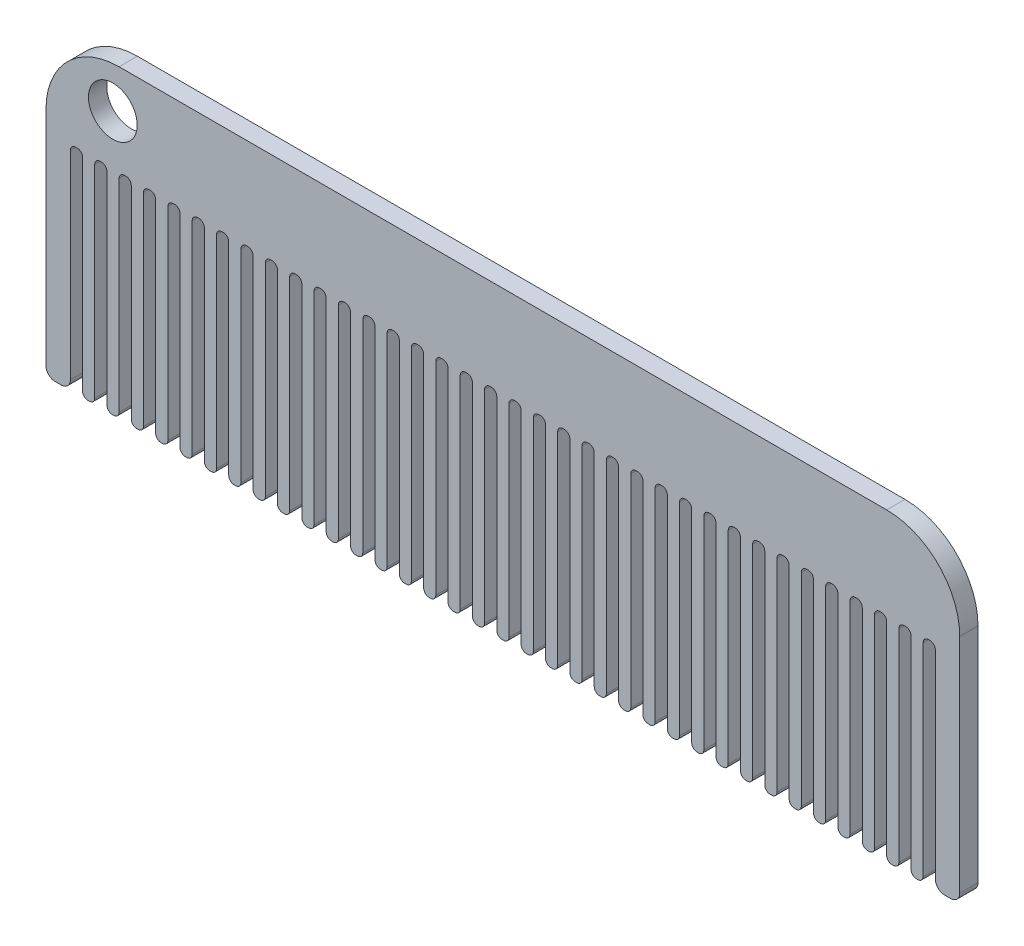
SolidWorks part; units mm, degrees
ref_plane "Plan de face" through (0, 0, 0) normal (0, 0, 1) x (1, 0, 0)
ref_plane "Plan de dessus" through (0, 0, 0) normal (0, 1, 0) x (1, 0, 0)
ref_plane "Plan de droite" through (0, 0, 0) normal (1, 0, 0) x (0, 0, -1)
sketch "Esquisse1" plane through (0, 0, 0) normal (0, 0, 1) x (1, 0, 0)
  line L1 (0, 1.5) -> (0, 38)
  line L2 (12, 50) -> (138, 50)
  line L3 (150, 38) -> (150, 1.5)
  line L4 (1.5, 0) -> (2.5, 0)
  line L5 (4, 1.5) -> (4, 34.12)
  line L6 (4.88, 35) -> (5.12, 35)
  line L7 (6, 34.12) -> (6, 0.88)
  line L8 (6.88, 0) -> (7.12, 0)
  line L9 (8, 0.88) -> (8, 34.12)
  line L10 (8.88, 35) -> (9.12, 35)
  line L11 (10, 34.12) -> (10, 0.88)
  line L12 (10.88, 0) -> (11.12, 0)
  line L13 (12, 0.88) -> (12, 34.12)
  line L14 (12.88, 35) -> (13.12, 35)
  line L15 (14, 34.12) -> (14, 0.88)
  line L16 (14.88, 0) -> (15.12, 0)
  line L17 (16, 0.88) -> (16, 34.12)
  line L18 (16.88, 35) -> (17.12, 35)
  line L19 (18, 34.12) -> (18, 0.88)
  line L20 (18.88, 0) -> (19.12, 0)
  line L21 (20, 0.88) -> (20, 34.12)
  line L22 (20.88, 35) -> (21.12, 35)
  line L23 (22, 34.12) -> (22, 0.88)
  line L24 (22.88, 0) -> (23.12, 0)
  line L25 (24, 0.88) -> (24, 34.12)
  line L26 (24.88, 35) -> (25.12, 35)
  line L27 (26, 34.12) -> (26, 0.88)
  line L28 (26.88, 0) -> (27.12, 0)
  line L29 (28, 0.88) -> (28, 34.12)
  line L30 (28.88, 35) -> (29.12, 35)
  line L31 (30, 34.12) -> (30, 0.88)
  line L32 (30.88, 0) -> (31.12, 0)
  line L33 (32, 0.88) -> (32, 34.12)
  line L34 (32.88, 35) -> (33.12, 35)
  line L35 (34, 34.12) -> (34, 0.88)
  line L36 (34.88, 0) -> (35.12, 0)
  line L37 (36, 0.88) -> (36, 34.12)
  line L38 (36.88, 35) -> (37.12, 35)
  line L39 (38, 34.12) -> (38, 0.88)
  line L40 (38.88, 0) -> (39.12, 0)
  line L41 (40, 0.88) -> (40, 34.12)
  line L42 (40.88, 35) -> (41.12, 35)
  line L43 (42, 34.12) -> (42, 0.88)
  line L44 (42.88, 0) -> (43.12, 0)
  line L45 (44, 0.88) -> (44, 34.12)
  line L46 (44.88, 35) -> (45.12, 35)
  line L47 (46, 34.12) -> (46, 0.88)
  line L48 (46.88, 0) -> (47.12, 0)
  line L49 (48, 0.88) -> (48, 34.12)
  line L50 (48.88, 35) -> (49.12, 35)
  line L51 (50, 34.12) -> (50, 0.88)
  line L52 (50.88, 0) -> (51.12, 0)
  line L53 (52, 0.88) -> (52, 34.12)
  line L54 (52.88, 35) -> (53.12, 35)
  line L55 (54, 34.12) -> (54, 0.88)
  line L56 (54.88, 0) -> (55.12, 0)
  line L57 (56, 0.88) -> (56, 34.12)
  line L58 (56.88, 35) -> (57.12, 35)
  line L59 (58, 34.12) -> (58, 0.88)
  line L60 (58.88, 0) -> (59.12, 0)
  line L61 (60, 0.88) -> (60, 34.12)
  line L62 (60.88, 35) -> (61.12, 35)
  line L63 (62, 34.12) -> (62, 0.88)
  line L64 (62.88, 0) -> (63.12, 0)
  line L65 (64, 0.88) -> (64, 34.12)
  line L66 (64.88, 35) -> (65.12, 35)
  line L67 (66, 34.12) -> (66, 0.88)
  line L68 (66.88, 0) -> (67.12, 0)
  line L69 (68, 0.88) -> (68, 34.12)
  line L70 (68.88, 35) -> (69.12, 35)
  line L71 (70, 34.12) -> (70, 0.88)
  line L72 (70.88, 0) -> (71.12, 0)
  line L73 (72, 0.88) -> (72, 34.12)
  line L74 (72.88, 35) -> (73.12, 35)
  line L75 (74, 34.12) -> (74, 0.88)
  line L76 (74.88, 0) -> (75.12, 0)
  line L77 (76, 0.88) -> (76, 34.12)
  line L78 (76.88, 35) -> (77.12, 35)
  line L79 (78, 34.12) -> (78, 0.88)
  line L80 (78.88, 0) -> (79.12, 0)
  line L81 (80, 0.88) -> (80, 34.12)
  line L82 (80.88, 35) -> (81.12, 35)
  line L83 (82, 34.12) -> (82, 0.88)
  line L84 (82.88, 0) -> (83.12, 0)
  line L85 (84, 0.88) -> (84, 34.12)
  line L86 (84.88, 35) -> (85.12, 35)
  line L87 (86, 34.12) -> (86, 0.88)
  line L88 (86.88, 0) -> (87.12, 0)
  line L89 (88, 0.88) -> (88, 34.12)
  line L90 (88.88, 35) -> (89.12, 35)
  line L91 (90, 34.12) -> (90, 0.88)
  line L92 (90.88, 0) -> (91.12, 0)
  line L93 (92, 0.88) -> (92, 34.12)
  line L94 (92.88, 35) -> (93.12, 35)
  line L95 (94, 34.12) -> (94, 0.88)
  line L96 (94.88, 0) -> (95.12, 0)
  line L97 (96, 0.88) -> (96, 34.12)
  line L98 (96.88, 35) -> (97.12, 35)
  line L99 (98, 34.12) -> (98, 0.88)
  line L100 (98.88, 0) -> (99.12, 0)
  line L101 (100, 0.88) -> (100, 34.12)
  line L102 (100.88, 35) -> (101.12, 35)
  line L103 (102, 34.12) -> (102, 0.88)
  line L104 (102.88, 0) -> (103.12, 0)
  line L105 (104, 0.88) -> (104, 34.12)
  line L106 (104.88, 35) -> (105.12, 35)
  line L107 (106, 34.12) -> (106, 0.88)
  line L108 (106.88, 0) -> (107.12, 0)
  line L109 (108, 0.88) -> (108, 34.12)
  line L110 (108.88, 35) -> (109.12, 35)
  line L111 (110, 34.12) -> (110, 0.88)
  line L112 (110.88, 0) -> (111.12, 0)
  line L113 (112, 0.88) -> (112, 34.12)
  line L114 (112.88, 35) -> (113.12, 35)
  line L115 (114, 34.12) -> (114, 0.88)
  line L116 (114.88, 0) -> (115.12, 0)
  line L117 (116, 0.88) -> (116, 34.12)
  line L118 (116.88, 35) -> (117.12, 35)
  line L119 (118, 34.12) -> (118, 0.88)
  line L120 (118.88, 0) -> (119.12, 0)
  line L121 (120, 0.88) -> (120, 34.12)
  line L122 (120.88, 35) -> (121.12, 35)
  line L123 (122, 34.12) -> (122, 0.88)
  line L124 (122.88, 0) -> (123.12, 0)
  line L125 (124, 0.88) -> (124, 34.12)
  line L126 (124.88, 35) -> (125.12, 35)
  line L127 (126, 34.12) -> (126, 0.88)
  line L128 (126.88, 0) -> (127.12, 0)
  line L129 (128, 0.88) -> (128, 34.12)
  line L130 (128.88, 35) -> (129.12, 35)
  line L131 (130, 34.12) -> (130, 0.88)
  line L132 (130.88, 0) -> (131.12, 0)
  line L133 (132, 0.88) -> (132, 34.12)
  line L134 (132.88, 35) -> (133.12, 35)
  line L135 (134, 34.12) -> (134, 0.88)
  line L136 (134.88, 0) -> (135.12, 0)
  line L137 (136, 0.88) -> (136, 34.12)
  line L138 (136.88, 35) -> (137.12, 35)
  line L139 (138, 34.12) -> (138, 0.88)
  line L140 (138.88, 0) -> (139.12, 0)
  line L141 (140, 0.88) -> (140, 34.12)
  line L142 (140.88, 35) -> (141.12, 35)
  line L143 (142, 34.12) -> (142, 0.88)
  line L144 (142.88, 0) -> (143.12, 0)
  line L145 (144, 0.88) -> (144, 34.12)
  line L146 (148.5, 0) -> (147.5, 0)
  line L147 (146, 1.5) -> (146, 34.12)
  line L148 (145.12, 35) -> (144.88, 35)
  arc A1 (12, 50) -> (0, 38) centre (12, 38) ccw
  arc A2 (138, 50) -> (150, 38) centre (138, 38) cw
  arc A3 (1.5, 0) -> (0, 1.5) centre (1.5, 1.5) cw
  arc A4 (4, 1.5) -> (2.5, 0) centre (2.5, 1.5) cw
  arc A5 (4, 34.12) -> (4.88, 35) centre (4.88, 34.12) cw
  arc A6 (5.12, 35) -> (6, 34.12) centre (5.12, 34.12) cw
  arc A7 (6, 0.88) -> (6.88, 0) centre (6.88, 0.88) ccw
  arc A8 (7.12, 0) -> (8, 0.88) centre (7.12, 0.88) ccw
  arc A9 (8, 34.12) -> (8.88, 35) centre (8.88, 34.12) cw
  arc A10 (9.12, 35) -> (10, 34.12) centre (9.12, 34.12) cw
  arc A11 (10, 0.88) -> (10.88, 0) centre (10.88, 0.88) ccw
  arc A12 (11.12, 0) -> (12, 0.88) centre (11.12, 0.88) ccw
  arc A13 (12, 34.12) -> (12.88, 35) centre (12.88, 34.12) cw
  arc A14 (13.12, 35) -> (14, 34.12) centre (13.12, 34.12) cw
  arc A15 (14, 0.88) -> (14.88, 0) centre (14.88, 0.88) ccw
  arc A16 (15.12, 0) -> (16, 0.88) centre (15.12, 0.88) ccw
  arc A17 (16, 34.12) -> (16.88, 35) centre (16.88, 34.12) cw
  arc A18 (17.12, 35) -> (18, 34.12) centre (17.12, 34.12) cw
  arc A19 (18, 0.88) -> (18.88, 0) centre (18.88, 0.88) ccw
  arc A20 (19.12, 0) -> (20, 0.88) centre (19.12, 0.88) ccw
  arc A21 (20, 34.12) -> (20.88, 35) centre (20.88, 34.12) cw
  arc A22 (21.12, 35) -> (22, 34.12) centre (21.12, 34.12) cw
  arc A23 (22, 0.88) -> (22.88, 0) centre (22.88, 0.88) ccw
  arc A24 (23.12, 0) -> (24, 0.88) centre (23.12, 0.88) ccw
  arc A25 (24, 34.12) -> (24.88, 35) centre (24.88, 34.12) cw
  arc A26 (25.12, 35) -> (26, 34.12) centre (25.12, 34.12) cw
  arc A27 (26, 0.88) -> (26.88, 0) centre (26.88, 0.88) ccw
  arc A28 (27.12, 0) -> (28, 0.88) centre (27.12, 0.88) ccw
  arc A29 (28, 34.12) -> (28.88, 35) centre (28.88, 34.12) cw
  arc A30 (29.12, 35) -> (30, 34.12) centre (29.12, 34.12) cw
  arc A31 (30, 0.88) -> (30.88, 0) centre (30.88, 0.88) ccw
  arc A32 (31.12, 0) -> (32, 0.88) centre (31.12, 0.88) ccw
  arc A33 (32, 34.12) -> (32.88, 35) centre (32.88, 34.12) cw
  arc A34 (33.12, 35) -> (34, 34.12) centre (33.12, 34.12) cw
  arc A35 (34, 0.88) -> (34.88, 0) centre (34.88, 0.88) ccw
  arc A36 (35.12, 0) -> (36, 0.88) centre (35.12, 0.88) ccw
  arc A37 (36, 34.12) -> (36.88, 35) centre (36.88, 34.12) cw
  arc A38 (37.12, 35) -> (38, 34.12) centre (37.12, 34.12) cw
  arc A39 (38, 0.88) -> (38.88, 0) centre (38.88, 0.88) ccw
  arc A40 (39.12, 0) -> (40, 0.88) centre (39.12, 0.88) ccw
  arc A41 (40, 34.12) -> (40.88, 35) centre (40.88, 34.12) cw
  arc A42 (41.12, 35) -> (42, 34.12) centre (41.12, 34.12) cw
  arc A43 (42, 0.88) -> (42.88, 0) centre (42.88, 0.88) ccw
  arc A44 (43.12, 0) -> (44, 0.88) centre (43.12, 0.88) ccw
  arc A45 (44, 34.12) -> (44.88, 35) centre (44.88, 34.12) cw
  arc A46 (45.12, 35) -> (46, 34.12) centre (45.12, 34.12) cw
  arc A47 (46, 0.88) -> (46.88, 0) centre (46.88, 0.88) ccw
  arc A48 (47.12, 0) -> (48, 0.88) centre (47.12, 0.88) ccw
  arc A49 (48, 34.12) -> (48.88, 35) centre (48.88, 34.12) cw
  arc A50 (49.12, 35) -> (50, 34.12) centre (49.12, 34.12) cw
  arc A51 (50, 0.88) -> (50.88, 0) centre (50.88, 0.88) ccw
  arc A52 (51.12, 0) -> (52, 0.88) centre (51.12, 0.88) ccw
  arc A53 (52, 34.12) -> (52.88, 35) centre (52.88, 34.12) cw
  arc A54 (53.12, 35) -> (54, 34.12) centre (53.12, 34.12) cw
  arc A55 (54, 0.88) -> (54.88, 0) centre (54.88, 0.88) ccw
  arc A56 (55.12, 0) -> (56, 0.88) centre (55.12, 0.88) ccw
  arc A57 (56, 34.12) -> (56.88, 35) centre (56.88, 34.12) cw
  arc A58 (57.12, 35) -> (58, 34.12) centre (57.12, 34.12) cw
  arc A59 (58, 0.88) -> (58.88, 0) centre (58.88, 0.88) ccw
  arc A60 (59.12, 0) -> (60, 0.88) centre (59.12, 0.88) ccw
  arc A61 (60, 34.12) -> (60.88, 35) centre (60.88, 34.12) cw
  arc A62 (61.12, 35) -> (62, 34.12) centre (61.12, 34.12) cw
  arc A63 (62, 0.88) -> (62.88, 0) centre (62.88, 0.88) ccw
  arc A64 (63.12, 0) -> (64, 0.88) centre (63.12, 0.88) ccw
  arc A65 (64, 34.12) -> (64.88, 35) centre (64.88, 34.12) cw
  arc A66 (65.12, 35) -> (66, 34.12) centre (65.12, 34.12) cw
  arc A67 (66, 0.88) -> (66.88, 0) centre (66.88, 0.88) ccw
  arc A68 (67.12, 0) -> (68, 0.88) centre (67.12, 0.88) ccw
  arc A69 (68, 34.12) -> (68.88, 35) centre (68.88, 34.12) cw
  arc A70 (69.12, 35) -> (70, 34.12) centre (69.12, 34.12) cw
  arc A71 (70, 0.88) -> (70.88, 0) centre (70.88, 0.88) ccw
  arc A72 (71.12, 0) -> (72, 0.88) centre (71.12, 0.88) ccw
  arc A73 (72, 34.12) -> (72.88, 35) centre (72.88, 34.12) cw
  arc A74 (73.12, 35) -> (74, 34.12) centre (73.12, 34.12) cw
  arc A75 (74, 0.88) -> (74.88, 0) centre (74.88, 0.88) ccw
  arc A76 (75.12, 0) -> (76, 0.88) centre (75.12, 0.88) ccw
  arc A77 (76, 34.12) -> (76.88, 35) centre (76.88, 34.12) cw
  arc A78 (77.12, 35) -> (78, 34.12) centre (77.12, 34.12) cw
  arc A79 (78, 0.88) -> (78.88, 0) centre (78.88, 0.88) ccw
  arc A80 (79.12, 0) -> (80, 0.88) centre (79.12, 0.88) ccw
  arc A81 (80, 34.12) -> (80.88, 35) centre (80.88, 34.12) cw
  arc A82 (81.12, 35) -> (82, 34.12) centre (81.12, 34.12) cw
  arc A83 (82, 0.88) -> (82.88, 0) centre (82.88, 0.88) ccw
  arc A84 (83.12, 0) -> (84, 0.88) centre (83.12, 0.88) ccw
  arc A85 (84, 34.12) -> (84.88, 35) centre (84.88, 34.12) cw
  arc A86 (85.12, 35) -> (86, 34.12) centre (85.12, 34.12) cw
  arc A87 (86, 0.88) -> (86.88, 0) centre (86.88, 0.88) ccw
  arc A88 (87.12, 0) -> (88, 0.88) centre (87.12, 0.88) ccw
  arc A89 (88, 34.12) -> (88.88, 35) centre (88.88, 34.12) cw
  arc A90 (89.12, 35) -> (90, 34.12) centre (89.12, 34.12) cw
  arc A91 (90, 0.88) -> (90.88, 0) centre (90.88, 0.88) ccw
  arc A92 (91.12, 0) -> (92, 0.88) centre (91.12, 0.88) ccw
  arc A93 (92, 34.12) -> (92.88, 35) centre (92.88, 34.12) cw
  arc A94 (93.12, 35) -> (94, 34.12) centre (93.12, 34.12) cw
  arc A95 (94, 0.88) -> (94.88, 0) centre (94.88, 0.88) ccw
  arc A96 (95.12, 0) -> (96, 0.88) centre (95.12, 0.88) ccw
  arc A97 (96, 34.12) -> (96.88, 35) centre (96.88, 34.12) cw
  arc A98 (97.12, 35) -> (98, 34.12) centre (97.12, 34.12) cw
  arc A99 (98, 0.88) -> (98.88, 0) centre (98.88, 0.88) ccw
  arc A100 (99.12, 0) -> (100, 0.88) centre (99.12, 0.88) ccw
  arc A101 (100, 34.12) -> (100.88, 35) centre (100.88, 34.12) cw
  arc A102 (101.12, 35) -> (102, 34.12) centre (101.12, 34.12) cw
  arc A103 (102, 0.88) -> (102.88, 0) centre (102.88, 0.88) ccw
  arc A104 (103.12, 0) -> (104, 0.88) centre (103.12, 0.88) ccw
  arc A105 (104, 34.12) -> (104.88, 35) centre (104.88, 34.12) cw
  arc A106 (105.12, 35) -> (106, 34.12) centre (105.12, 34.12) cw
  arc A107 (106, 0.88) -> (106.88, 0) centre (106.88, 0.88) ccw
  arc A108 (107.12, 0) -> (108, 0.88) centre (107.12, 0.88) ccw
  arc A109 (108, 34.12) -> (108.88, 35) centre (108.88, 34.12) cw
  arc A110 (109.12, 35) -> (110, 34.12) centre (109.12, 34.12) cw
  arc A111 (110, 0.88) -> (110.88, 0) centre (110.88, 0.88) ccw
  arc A112 (111.12, 0) -> (112, 0.88) centre (111.12, 0.88) ccw
  arc A113 (112, 34.12) -> (112.88, 35) centre (112.88, 34.12) cw
  arc A114 (113.12, 35) -> (114, 34.12) centre (113.12, 34.12) cw
  arc A115 (114, 0.88) -> (114.88, 0) centre (114.88, 0.88) ccw
  arc A116 (115.12, 0) -> (116, 0.88) centre (115.12, 0.88) ccw
  arc A117 (116, 34.12) -> (116.88, 35) centre (116.88, 34.12) cw
  arc A118 (117.12, 35) -> (118, 34.12) centre (117.12, 34.12) cw
  arc A119 (118, 0.88) -> (118.88, 0) centre (118.88, 0.88) ccw
  arc A120 (119.12, 0) -> (120, 0.88) centre (119.12, 0.88) ccw
  arc A121 (120, 34.12) -> (120.88, 35) centre (120.88, 34.12) cw
  arc A122 (121.12, 35) -> (122, 34.12) centre (121.12, 34.12) cw
  arc A123 (122, 0.88) -> (122.88, 0) centre (122.88, 0.88) ccw
  arc A124 (123.12, 0) -> (124, 0.88) centre (123.12, 0.88) ccw
  arc A125 (124, 34.12) -> (124.88, 35) centre (124.88, 34.12) cw
  arc A126 (125.12, 35) -> (126, 34.12) centre (125.12, 34.12) cw
  arc A127 (126, 0.88) -> (126.88, 0) centre (126.88, 0.88) ccw
  arc A128 (127.12, 0) -> (128, 0.88) centre (127.12, 0.88) ccw
  arc A129 (128, 34.12) -> (128.88, 35) centre (128.88, 34.12) cw
  arc A130 (129.12, 35) -> (130, 34.12) centre (129.12, 34.12) cw
  arc A131 (130, 0.88) -> (130.88, 0) centre (130.88, 0.88) ccw
  arc A132 (131.12, 0) -> (132, 0.88) centre (131.12, 0.88) ccw
  arc A133 (132, 34.12) -> (132.88, 35) centre (132.88, 34.12) cw
  arc A134 (133.12, 35) -> (134, 34.12) centre (133.12, 34.12) cw
  arc A135 (134, 0.88) -> (134.88, 0) centre (134.88, 0.88) ccw
  arc A136 (135.12, 0) -> (136, 0.88) centre (135.12, 0.88) ccw
  arc A137 (136, 34.12) -> (136.88, 35) centre (136.88, 34.12) cw
  arc A138 (137.12, 35) -> (138, 34.12) centre (137.12, 34.12) cw
  arc A139 (138, 0.88) -> (138.88, 0) centre (138.88, 0.88) ccw
  arc A140 (139.12, 0) -> (140, 0.88) centre (139.12, 0.88) ccw
  arc A141 (140, 34.12) -> (140.88, 35) centre (140.88, 34.12) cw
  arc A142 (141.12, 35) -> (142, 34.12) centre (141.12, 34.12) cw
  arc A143 (142, 0.88) -> (142.88, 0) centre (142.88, 0.88) ccw
  arc A144 (143.12, 0) -> (144, 0.88) centre (143.12, 0.88) ccw
  arc A145 (148.5, 0) -> (150, 1.5) centre (148.5, 1.5) ccw
  arc A146 (146, 1.5) -> (147.5, 0) centre (147.5, 1.5) ccw
  arc A147 (144.88, 35) -> (144, 34.12) centre (144.88, 34.12) ccw
  arc A148 (145.12, 35) -> (146, 34.12) centre (145.12, 34.12) cw
  point P10 (150, 19.75)
  point P16 (0, 0)
  point P19 (4, 0)
  point P23 (4, 35)
  point P74 (150, 0)
  point P113 (146, 0)
  dimension "D1" = 12
  dimension "D6" = 1.5
  dimension "D7" = 0.88
  dimension "D10" = 0.88
  dimension "D13" = 1.5
  dimension "D14" = 0.88
  dimension "D2" = 150
  dimension "D3" = 50
  dimension "D4" = 35
  dimension "D5" = 4
  dimension "D8" = 2
  dimension "D9" = 2
  dimension "D12" = 4
  dimension "D11" = 35
extrude "Boss.-Extru.1" add sketch "Esquisse1" along normal blind 3 contours L2 A2 L3 A145 L146 A146 L147 A148 L148 A147 L145 A144 L144 A143 L143 A142 L142 A141 L141 A140 L140 A139 L139 A138 L138 A137 L137 A136 L136 A135 L135 A134 L134 A133 L133 A132 L132 A131 L131 A130 L130 A129 L129 A128 L128 A127 L127 A126 L126 A125 L125 A124 L124 A123 L123 A122 L122 A121 L121 A120 L120 A119 L119 A118 L118 A117 L117 A116 L116 A115 L115 A114 L114 A113 L113 A112 L112 A111 L111 A110 L110 A109 L109 A108 L108 A107 L107 A106 L106 A105 L105 A104 L104 A103 L103 A102 L102 A101 L101 A100 L100 A99 L99 A98 L98 A97 L97 A96 L96 A95 L95 A94 L94 A93 L93 A92 L92 A91 L91 A90 L90 A89 L89 A88 L88 A87 L87 A86 L86 A85 L85 A84 L84 A83 L83 A82 L82 A81 L81 A80 L80 A79 L79 A78 L78 A77 L77 A76 L76 A75 L75 A74 L74 A73 L73 A72 L72 A71 L71 A70 L70 A69 L69 A68 L68 A67 L67 A66 L66 A65 L65 A64 L64 A63 L63 A62 L62 A61 L61 A60 L60 A59 L59 A58 L58 A57 L57 A56 L56 A55 L55 A54 L54 A53 L53 A52 L52 A51 L51 A50 L50 A49 L49 A48 L48 A47 L47 A46 L46 A45 L45 A44 L44 A43 L43 A42 L42 A41 L41 A40 L40 A39 L39 A38 L38 A37 L37 A36 L36 A35 L35 A34 L34 A33 L33 A32 L32 A31 L31 A30 L30 A29 L29 A28 L28 A27 L27 A26 L26 A25 L25 A24 L24 A23 L23 A22 L22 A21 L21 A20 L20 A19 L19 A18 L18 A17 L17 A16 L16 A15 L15 A14 L14 A13 L13 A12 L12 A11 L11 A10 L10 A9 L9 A8 L8 A7 L7 A6 L6 A5 L5 A4 L4 A3 L1 A1
sketch "Esquisse2" plane through (0, 0, 3) normal (0, 0, 1) x (1, 0, 0)
  circle A0 centre (10.9692, 43.1749) radius 4
  dimension "D1" = 8
extrude "Enlèv. mat.-Extru.1" cut sketch "Esquisse2" against normal blind 10
